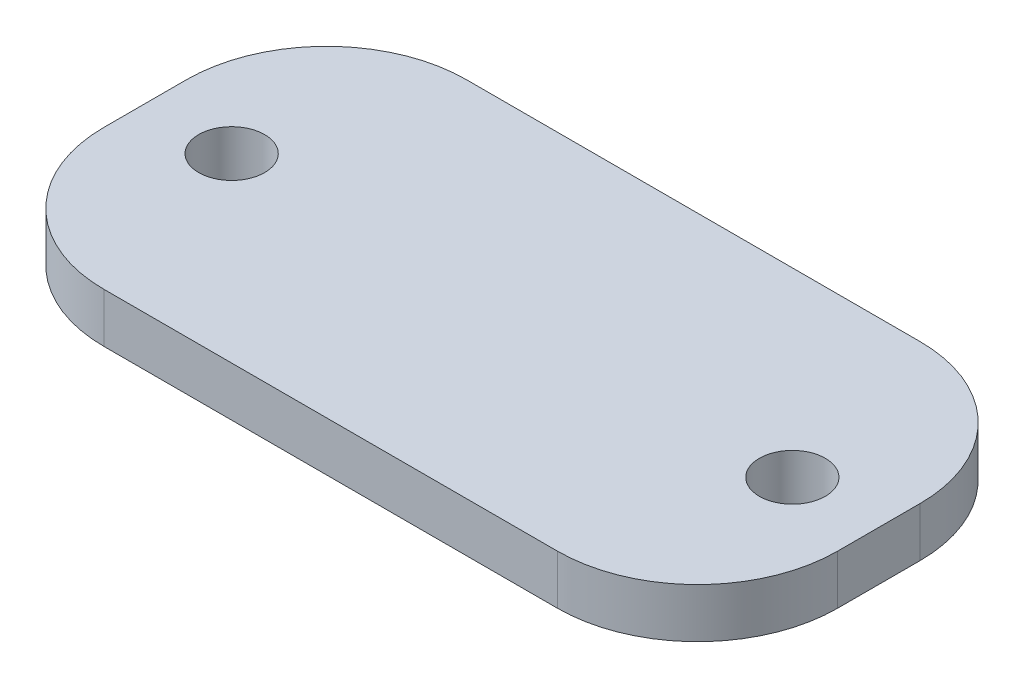
SolidWorks part; units mm, degrees
ref_plane "Plano frontal" through (0, 0, 0) normal (0, 0, 1) x (1, 0, 0)
ref_plane "Plano superior" through (0, 0, 0) normal (0, 1, 0) x (1, 0, 0)
ref_plane "Plano direito" through (0, 0, 0) normal (1, 0, 0) x (0, 0, -1)
sketch "Esboço1" plane through (0, 0, 0) normal (0, 1, 0) x (1, 0, 0)
  line L1 (-22.25, 11) -> (22.25, 11)
  line L2 (-22.25, 11) -> (-22.25, -11)
  line L3 (-22.25, -11) -> (22.25, -11)
  line L4 (22.25, 11) -> (22.25, -11)
  line L5 (-22.25, 11) -> (22.25, -11) construction
  line L6 (-22.25, -11) -> (22.25, 11) construction
  point P0 (0, 0)
  dimension "D1" = 22
  dimension "D2" = 44.5
extrude "Ressalto-extrusão1" add sketch "Esboço1" along normal blind 3
fillet "Filete1" radius 8.5 4 edges at (22.25, 1.5, -11) (22.25, 1.5, 11) (-22.25, 1.5, 11) (-22.25, 1.5, -11)
sketch "Esboço2" plane through (0, 3, 0) normal (0, 1, 0) x (1, 0, 0)
  line L0 (13.75, 11) -> (-13.75, 11) construction
  line L1 (-22.25, 2.5) -> (-22.25, -2.5) construction
  line L2 (22.25, -2.5) -> (22.25, 2.5) construction
  circle A0 centre (-17, 0) radius 2
  circle A1 centre (17, 0) radius 2
  dimension "D1" = 4
  dimension "D2" = 4
  dimension "D4" = 11
  dimension "D7" = 11
  dimension "D3" = 44.5
  dimension "D5" = 5.25
  dimension "D6" = 34
extrude "Corte-extrusão1" cut sketch "Esboço2" against normal through all
